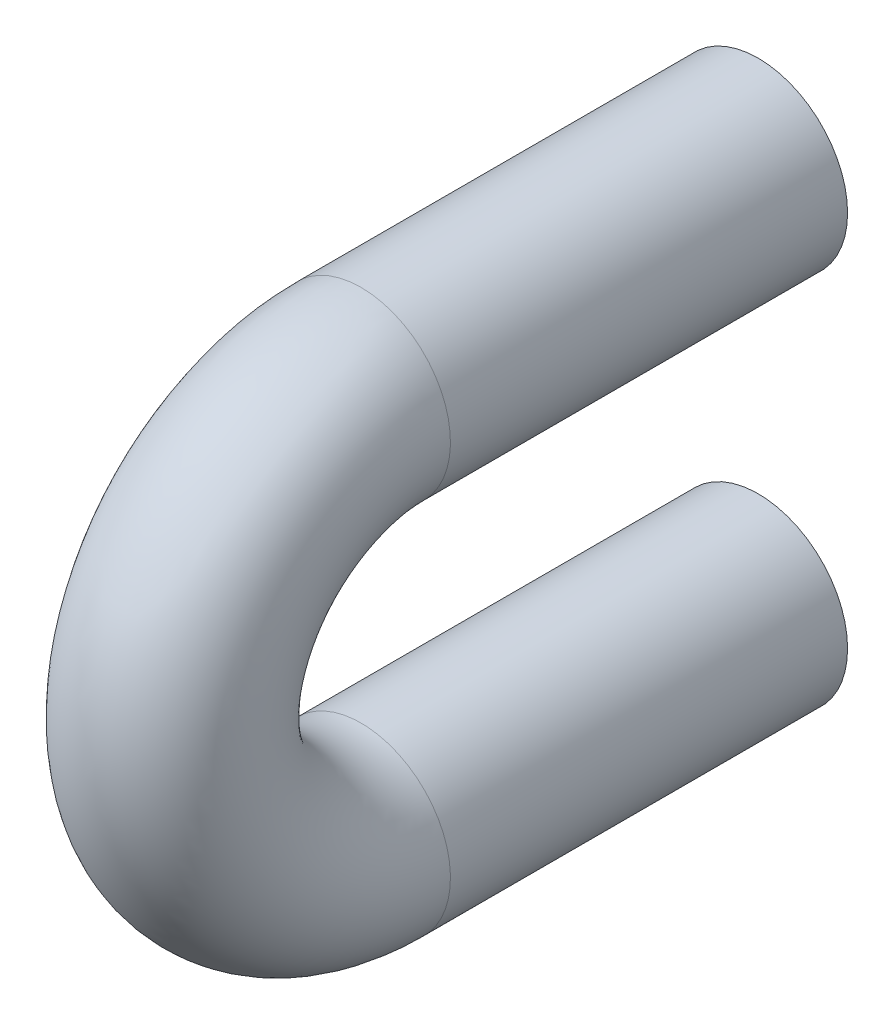
SolidWorks part; units mm, degrees
ref_plane "Plan1" through (0, 0, 0) normal (0, 0, 1) x (1, 0, 0)
ref_plane "Plan2" through (0, 0, 0) normal (0, 1, 0) x (1, 0, 0)
ref_plane "Plan3" through (0, 0, 0) normal (1, 0, 0) x (0, 0, -1)
sketch "Esquisse2" plane through (0, 0, 0) normal (0, 0, 1) x (1, 0, 0)
  circle A0 centre (0, 0) radius 4.5
sketch "Esquisse3" plane through (0, 0, 0) normal (1, 0, 0) x (0, 0, -1)
  line L0 (0, 0) -> (-20, 0)
  line L1 (-20, 19) -> (0, 19)
  arc A0 (-20, 0) -> (-20, 19) centre (-20, 9.5) cw
sweep "Base-Balayage" add profiles "Esquisse2" path "Esquisse3"
sketch "Esquisse4" plane through (0, 0, 0) normal (0, 0, -1) x (-1, 0, 0)
  circle A0 centre (0, 19) radius 3
  circle A1 centre (0, 0) radius 3
extrude "Enlèv. mat.-Extru.1" cut sketch "Esquisse4" against normal blind 18
